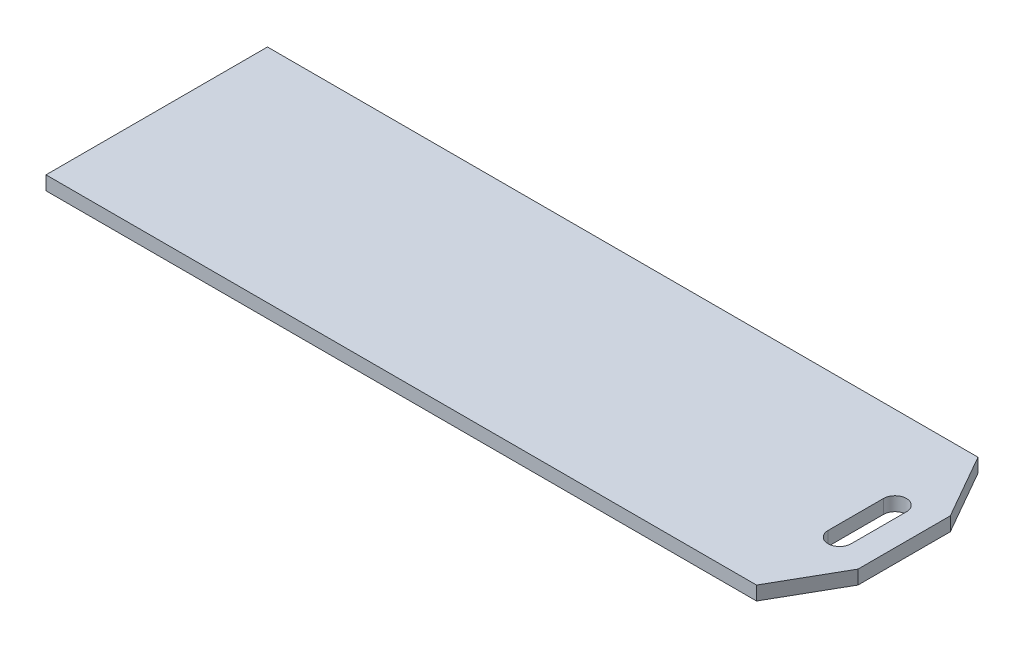
SolidWorks part; units mm, degrees
material "Pine"
ref_plane "Front Plane" through (0, 0, 0) normal (0, 0, 1) x (1, 0, 0)
ref_plane "Top Plane" through (0, 0, 0) normal (0, 1, 0) x (1, 0, 0)
ref_plane "Right Plane" through (0, 0, 0) normal (1, 0, 0) x (0, 0, -1)
sketch "Sketch1" plane through (0, 0, 0) normal (0, 1, 0) x (1, 0, 0)
  line L0 (0, 0) -> (977.9, 0)
  line L1 (0, 0) -> (0, -304.8)
  line L2 (0, -304.8) -> (977.9, -304.8)
  line L5 (977.9, 0) -> (1028.7, -88.9)
  line L6 (1028.7, -88.9) -> (1028.7, -215.9)
  line L7 (1028.7, -215.9) -> (977.9, -304.8)
  dimension "D1" = 304.8
  dimension "D2" = 977.9
  dimension "D3" = 977.9
  dimension "D4" = 127
extrude "Boss-Extrude1" add sketch "Sketch1" along normal blind 19.05
sketch "Sketch2" plane through (0, 19.05, 0) normal (0, 1, 0) x (1, 0, 0)
  line L3 (977.9, -114.3) -> (977.9, -190.5) construction
  line L4 (993.775, -114.3) -> (993.775, -190.5)
  line L5 (962.025, -114.3) -> (962.025, -190.5)
  arc A0 (993.775, -114.3) -> (962.025, -114.3) centre (977.9, -114.3) ccw
  arc A1 (962.025, -190.5) -> (993.775, -190.5) centre (977.9, -190.5) ccw
  point P5 (977.9, -152.4)
extrude "Cut-Extrude1" cut sketch "Sketch2" against normal blind 19.05
